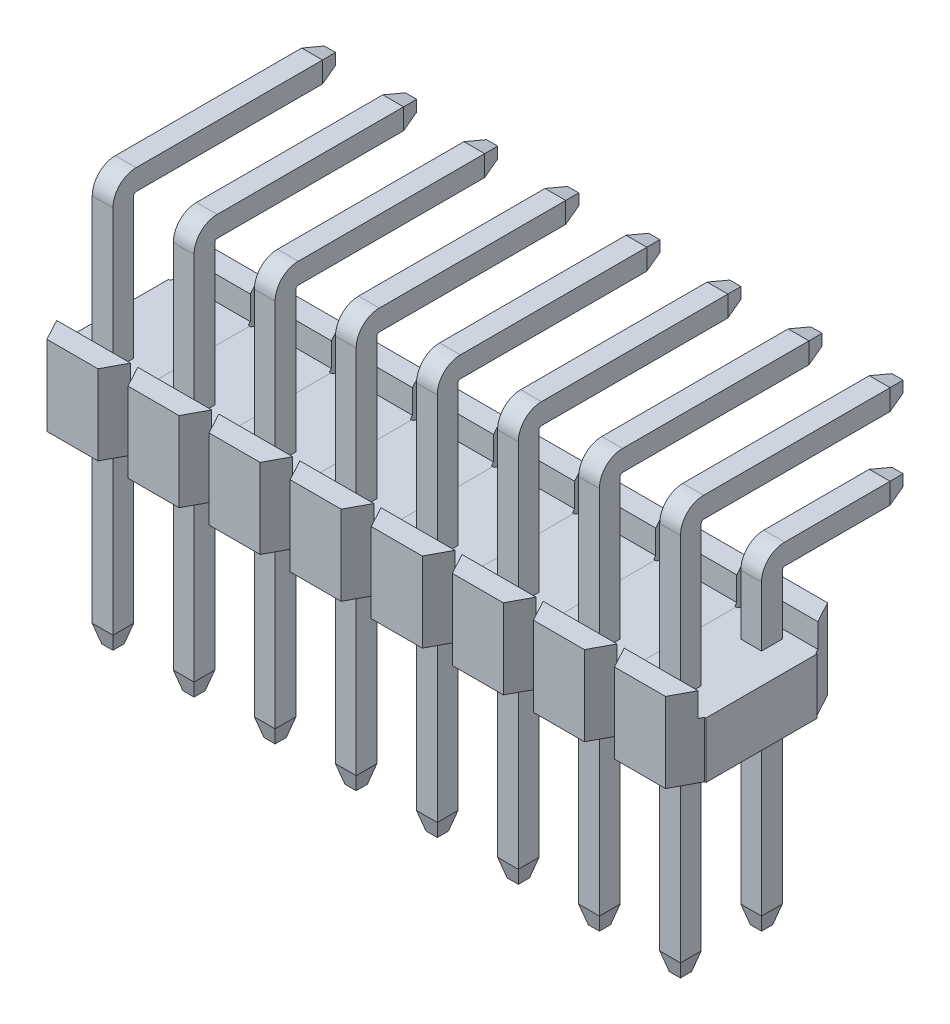
SolidWorks part; units mm, degrees
ref_plane "Спереди" through (0, 0, 0) normal (0, 0, 1) x (1, 0, 0)
ref_plane "Сверху" through (0, 0, 0) normal (0, 1, 0) x (1, 0, 0)
ref_plane "Справа" through (0, 0, 0) normal (1, 0, 0) x (0, 0, -1)
sketch "Эскиз1" plane through (0, 0, 0) normal (0, 1, 0) x (1, 0, 0)
  line L0 (-0.8, -5.08) -> (0.8, -5.08)
  line L1 (0.8, -5.08) -> (1.23, -4.28)
  line L2 (1.23, -4.28) -> (1.27, -4.28)
  line L3 (-1.27, -4.28) -> (-1.27, -0.8)
  line L4 (1.27, -4.28) -> (1.27, -0.8)
  line L5 (-1.23, -4.28) -> (-1.27, -4.28)
  line L6 (0, -2.54) -> (1.27, -2.54) construction
  line L7 (-0.8, -5.08) -> (-1.23, -4.28)
  line L8 (1.23, -0.8) -> (1.27, -0.8)
  line L9 (0.8, 0) -> (1.23, -0.8)
  line L10 (0, -5.08) -> (0, -2.54) construction
  line L11 (-0.8, 0) -> (0.8, 0)
  line L12 (-0.8, 0) -> (-1.23, -0.8)
  line L13 (-1.23, -0.8) -> (-1.27, -0.8)
  point P16 (-1.27, -2.54)
  dimension "D1" = 1.27
  dimension "D2" = 1.23
  dimension "D3" = 0.8
  dimension "D4" = 0.8
  dimension "D5" = 2.54
sketch "Эскиз3" plane through (0, 0, 0) normal (1, 0, 0) x (0, 0, -1)
  line L0 (2.99, 0) -> (-3.41, 0)
  line L1 (-3.81, -12.56) -> (-1.27, -12.56) construction
  line L2 (-3.81, -12.56) -> (-3.81, -0.4)
  line L5 (2.99, -2.54) -> (-0.87, -2.54) construction
  line L7 (-1.27, -12.56) -> (-1.27, -2.94) construction
  arc A1 (-3.41, 0) -> (-3.81, -0.4) centre (-3.41, -0.4) ccw
  arc A2 (-0.87, -2.54) -> (-1.27, -2.94) centre (-0.87, -2.94) ccw construction
  point P6 (-2.54, -12.56)
  dimension "D5" = 0.4
  dimension "D1" = 12.56
  dimension "D4" = 6.8
  dimension "D6" = 2.54
  dimension "D7" = 2.54
ref_plane "Плоскость1" through (0, -12.56, 0) normal (0, 1, 0) x (1, 0, 0)
sketch "Эскиз2" plane through (0, -12.56, 0) normal (0, 1, 0) x (1, 0, 0)
  line L1 (-0.325, -4.135) -> (0.325, -4.135)
  line L2 (-0.325, -4.135) -> (-0.325, -3.485)
  line L3 (-0.325, -3.485) -> (0.325, -3.485)
  line L4 (0.325, -4.135) -> (0.325, -3.485)
  line L5 (-0.325, -4.135) -> (0.325, -3.485) construction
  line L6 (-0.325, -3.485) -> (0.325, -4.135) construction
  line L7 (0, -3.81) -> (0, -1.27) construction
  line L8 (-0.325, -1.595) -> (0.325, -1.595) construction
  line L9 (-0.325, -1.595) -> (-0.325, -0.945) construction
  line L10 (-0.325, -0.945) -> (0.325, -0.945) construction
  line L11 (0.325, -1.595) -> (0.325, -0.945) construction
  line L12 (-0.325, -1.595) -> (0.325, -0.945) construction
  line L13 (-0.325, -0.945) -> (0.325, -1.595) construction
  point P0 (0, -3.81)
  point P7 (0, -1.27)
  dimension "D1" = 0.65
  dimension "D2" = 2.54
sketch "Эскиз4" plane through (0, -12.56, 0) normal (0, 1, 0) x (1, 0, 0)
  line L0 (0.325, -1.595) -> (0.325, -0.945) construction
  line L1 (-0.325, -1.595) -> (0.325, -1.595) construction
  line L2 (-0.325, -1.595) -> (-0.325, -0.945) construction
  line L3 (-0.325, -0.945) -> (0.325, -0.945) construction
  line L4 (0.325, -1.595) -> (0.325, -0.945)
  line L5 (-0.325, -1.595) -> (0.325, -1.595)
  line L6 (-0.325, -1.595) -> (-0.325, -0.945)
  line L7 (-0.325, -0.945) -> (0.325, -0.945)
sketch "Эскиз5" plane through (0, 0, 0) normal (1, 0, 0) x (0, 0, -1)
  line L0 (-1.27, -12.56) -> (-1.27, -2.94) construction
  line L1 (2.99, -2.54) -> (-0.87, -2.54) construction
  line L2 (-1.27, -12.56) -> (-1.27, -2.94)
  line L3 (2.99, -2.54) -> (-0.87, -2.54)
  arc A0 (-0.87, -2.54) -> (-1.27, -2.94) centre (-0.87, -2.94) ccw construction
  arc A1 (-0.87, -2.54) -> (-1.27, -2.94) centre (-0.87, -2.94) ccw
extrude "Бобышка-Вытянуть2" add sketch "Эскиз1" against normal blind 2.5 from offset 4.06 separate body offset against normal yes
sketch "Эскиз6" plane through (0, 0, 0) normal (0, 1, 0) x (1, 0, 0)
  line L0 (-1.27, -4.28) -> (-1.27, -0.8) construction
  line L1 (-1.27, -0.665) -> (1.27, -0.665)
  line L2 (-1.27, -0.665) -> (-1.27, -4.415)
  line L3 (-1.27, -4.415) -> (1.27, -4.415)
  line L4 (1.27, -0.665) -> (1.27, -4.415)
  line L5 (1.27, -4.28) -> (1.27, -0.8) construction
  dimension "D1" = 3.75
extrude "Вырез-Вытянуть1" cut sketch "Эскиз6" against normal blind 0.75 from offset 4.06 offset against normal yes
sweep "По траектории7" add profiles "Эскиз2" path "Эскиз3"
sweep "По траектории8" add profiles "Эскиз4" path "Эскиз5"
chamfer "Фаска5" distance 0.15 angle 75 4 edges at (0, -2.215, -2.99) (0.325, -2.54, -2.99) (0, -2.865, -2.99) (-0.325, -2.54, -2.99)
chamfer "Фаска6" distance 0.15 angle 75 4 edges at (0.325, 0, -2.99) (0, 0.325, -2.99) (-0.325, 0, -2.99) (0, -0.325, -2.99)
chamfer "Фаска7" distance 0.15 angle 75 4 edges at (0.325, -12.56, 3.81) (0, -12.56, 3.485) (-0.325, -12.56, 3.81) (0, -12.56, 4.135)
chamfer "Фаска8" distance 0.15 angle 75 4 edges at (0.325, -12.56, 1.27) (0, -12.56, 0.945) (-0.325, -12.56, 1.27) (0, -12.56, 1.595)
pattern_linear "Линейный массив1" count 8 spacing 2.54 along (-1, 0, 0) of bodies 112
